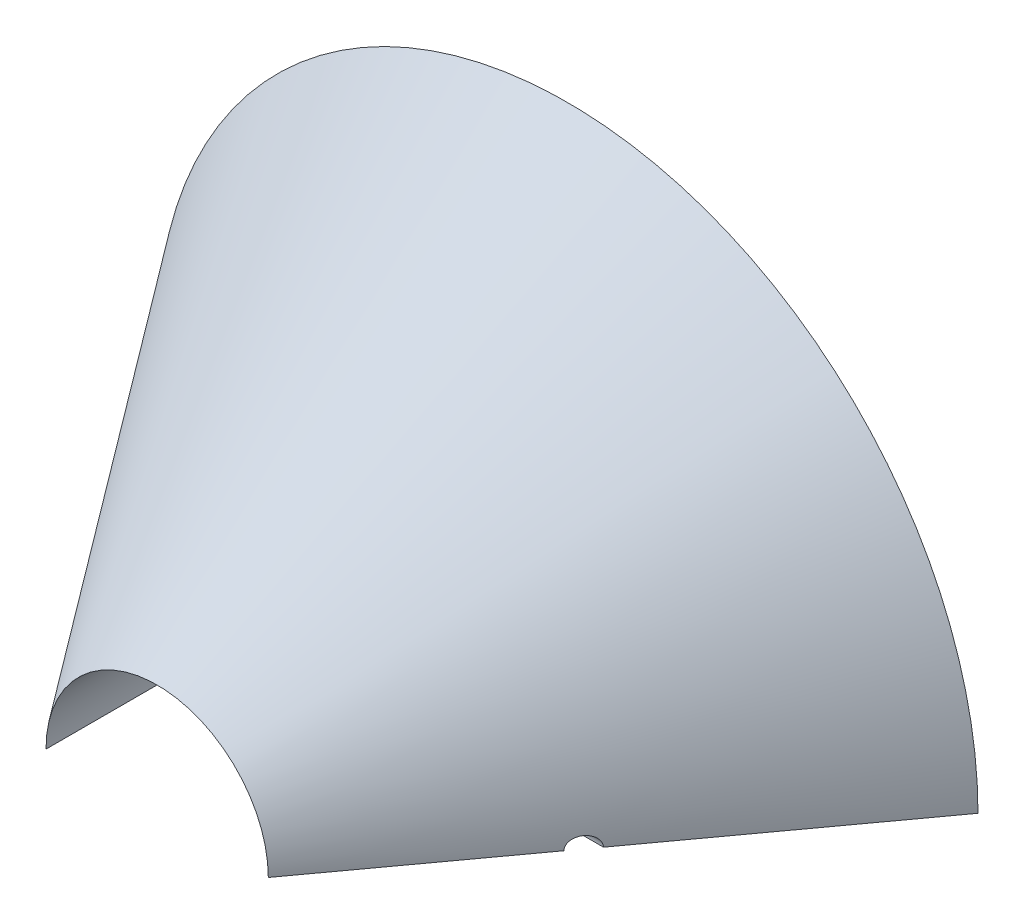
SolidWorks part; units mm, degrees
ref_plane "Plan de face" through (0, 0, 0) normal (0, 0, 1) x (1, 0, 0)
ref_plane "Plan de dessus" through (0, 0, 0) normal (0, 1, 0) x (1, 0, 0)
ref_plane "Plan de droite" through (0, 0, 0) normal (1, 0, 0) x (0, 0, -1)
sketch "Esquisse1" plane through (0, 0, 0) normal (0, 0, 1) x (1, 0, 0)
  circle A0 centre (0, 0) radius 180
  circle A1 centre (0, 0) radius 48.75
  dimension "D1" = 360
  dimension "D2" = 97.5
ref_plane "Plan1" through (0, 0, 180) normal (0, 0, 1) x (1, 0, 0)
sketch "Esquisse2" plane through (0, 0, 180) normal (0, 0, 1) x (1, 0, 0)
  circle A0 centre (0, 0) radius 48.75
  dimension "D1" = 97.5
sketch "Esquisse4" plane through (0, 0, 0) normal (1, 0, 0) x (0, 0, -1)
  line L0 (-180, 48.75) -> (0, 180)
  line L6 (-180, 48.75) -> (0, 48.75)
  line L9 (0, 48.75) -> (0, 180)
ref_axis "Axe1" through (0, 0, 180) along (0, 0, -1)
revolve "Révolution1" add sketch "Esquisse4" angle 360 about axis through (0, 0, 180) along (0, 0, -1)
ref_plane "Plan2" through (0, 0, 100) normal (0, 0, 1) x (1, 0, 0)
sketch "Esquisse6" plane through (0, 0, 100) normal (0, 0, 1) x (1, 0, 0)
  line L0 (0, 0) -> (274.7687, 64.6899)
  point P2 (0, 0)
  point P4 (0, 0)
  point P5 (111.0151, 13.8561)
  point P6 (0, 0)
  point P7 (274.7687, 64.6899)
sketch "Esquisse7" plane through (0, 0, 0) normal (1, 0, 0) x (0, 0, -1)
  circle A0 centre (-100, 0) radius 5
  point P2 (0, 0)
  dimension "D1" = 10
extrude "Enlèv. mat.-Extru.1" cut sketch "Esquisse7" along normal up to surface (110.7291 mm away) contours A0
other "Enlèv. mat.-Surface1"
